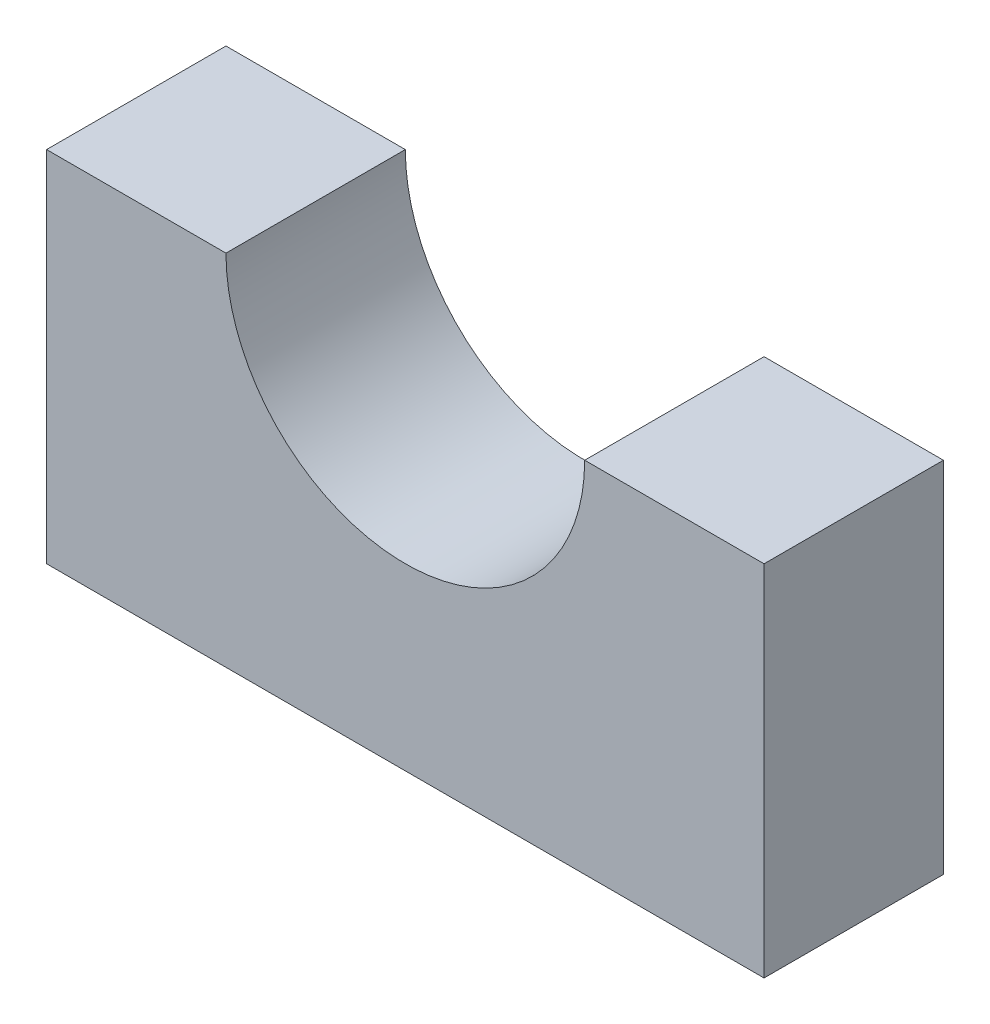
SolidWorks part; units mm, degrees
ref_plane "Front Plane" through (0, 0, 0) normal (0, 0, 1) x (1, 0, 0)
ref_plane "Top Plane" through (0, 0, 0) normal (0, 1, 0) x (1, 0, 0)
ref_plane "Right Plane" through (0, 0, 0) normal (1, 0, 0) x (0, 0, -1)
sketch "Sketch1" plane through (0, 0, 0) normal (0, 0, 1) x (1, 0, 0)
  line L0 (105, 70) -> (140, 70)
  line L1 (0, 0) -> (140, 0)
  line L2 (0, 0) -> (0, 70)
  line L3 (0, 70) -> (35, 70)
  line L4 (140, 0) -> (140, 70)
  arc A0 (105, 70) -> (35, 70) centre (70, 70) cw
  dimension "D4" = 35
  dimension "D1" = 70
  dimension "D2" = 140
  dimension "D3" = 35
extrude "Boss-Extrude1" add sketch "Sketch1" along normal blind 35
